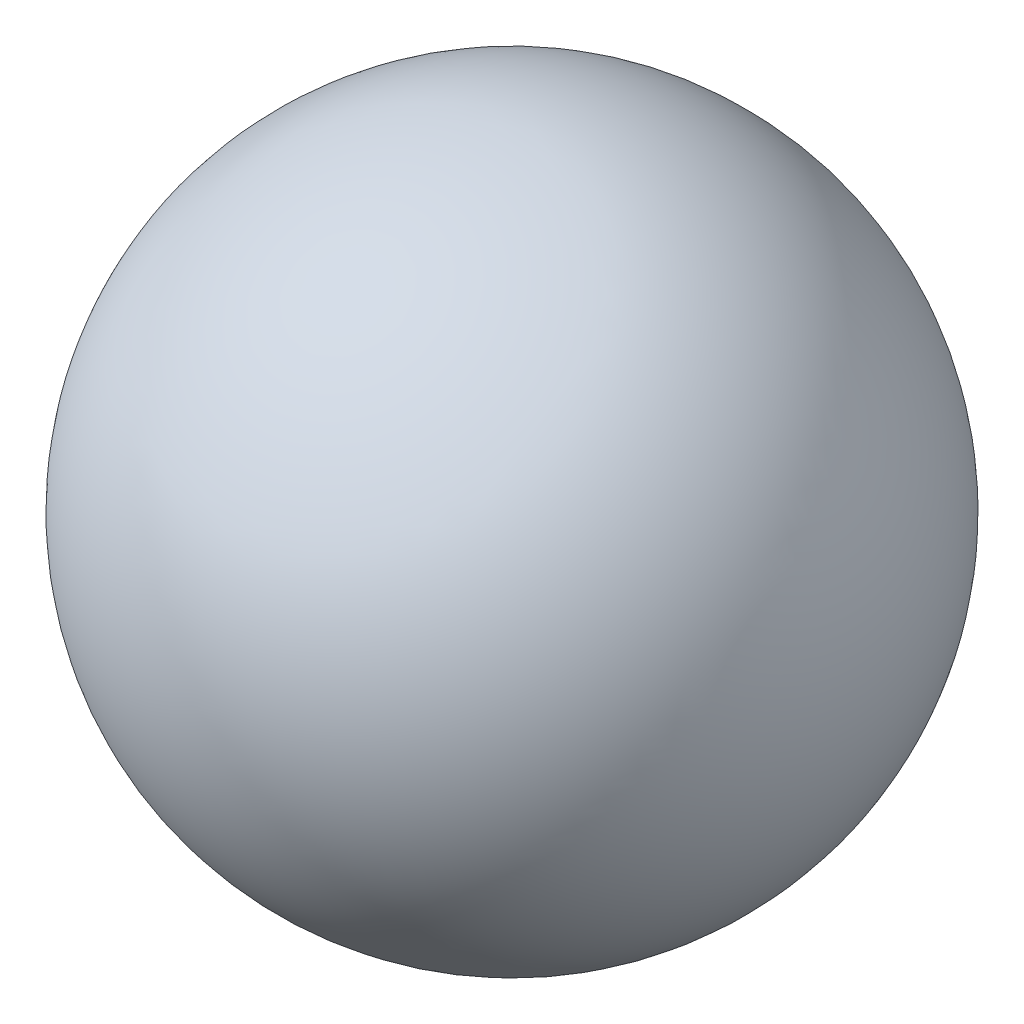
SolidWorks part; units mm, degrees
material "Tin Bearing Bronze"
ref_plane "Front Plane" through (0, 0, 0) normal (0, 0, 1) x (1, 0, 0)
ref_plane "Top Plane" through (0, 0, 0) normal (0, 1, 0) x (1, 0, 0)
ref_plane "Right Plane" through (0, 0, 0) normal (1, 0, 0) x (0, 0, -1)
sketch "Sketch1" plane through (0, 0, 0) normal (0, 1, 0) x (1, 0, 0)
  line L0 (0.762, 0) -> (-0.762, 0)
  arc A0 (0.762, 0) -> (-0.762, 0) centre (0, 0) ccw
  dimension "D1" = 0.762
revolve "Revolve2" add sketch "Sketch1" angle 360 about L0
